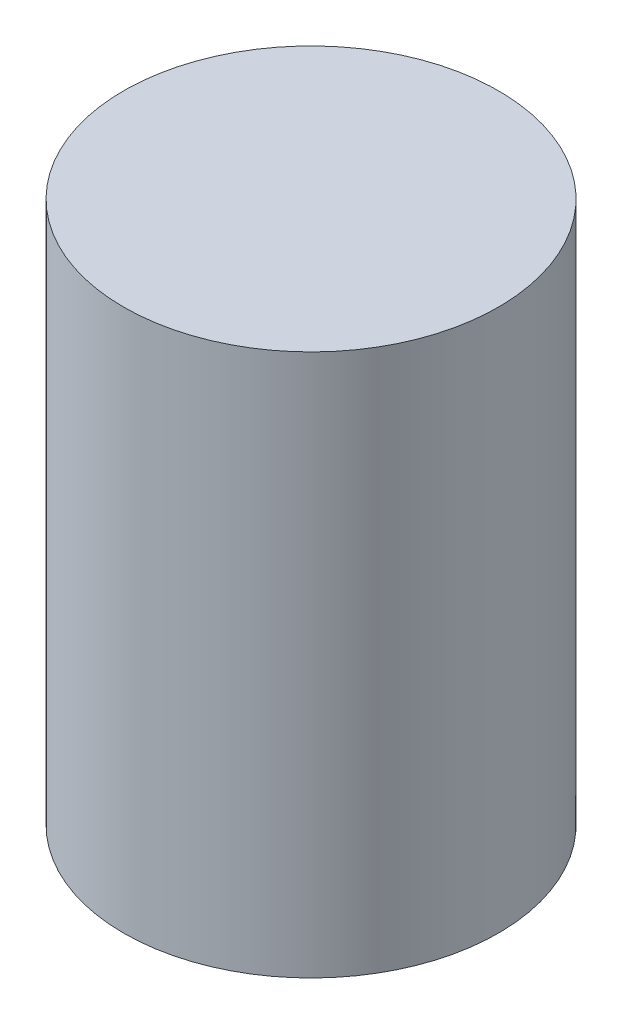
SolidWorks part; units mm, degrees
ref_plane "Front Plane" through (0, 0, 0) normal (0, 0, 1) x (1, 0, 0)
ref_plane "Top Plane" through (0, 0, 0) normal (0, 1, 0) x (1, 0, 0)
ref_plane "Right Plane" through (0, 0, 0) normal (1, 0, 0) x (0, 0, -1)
sketch "Sketch1" plane through (0, 0, 0) normal (0, 1, 0) x (1, 0, 0)
  circle A0 centre (0, 0) radius 15
  dimension "D1" = 30
extrude "Boss-Extrude1" add sketch "Sketch1" along normal blind 43.4
